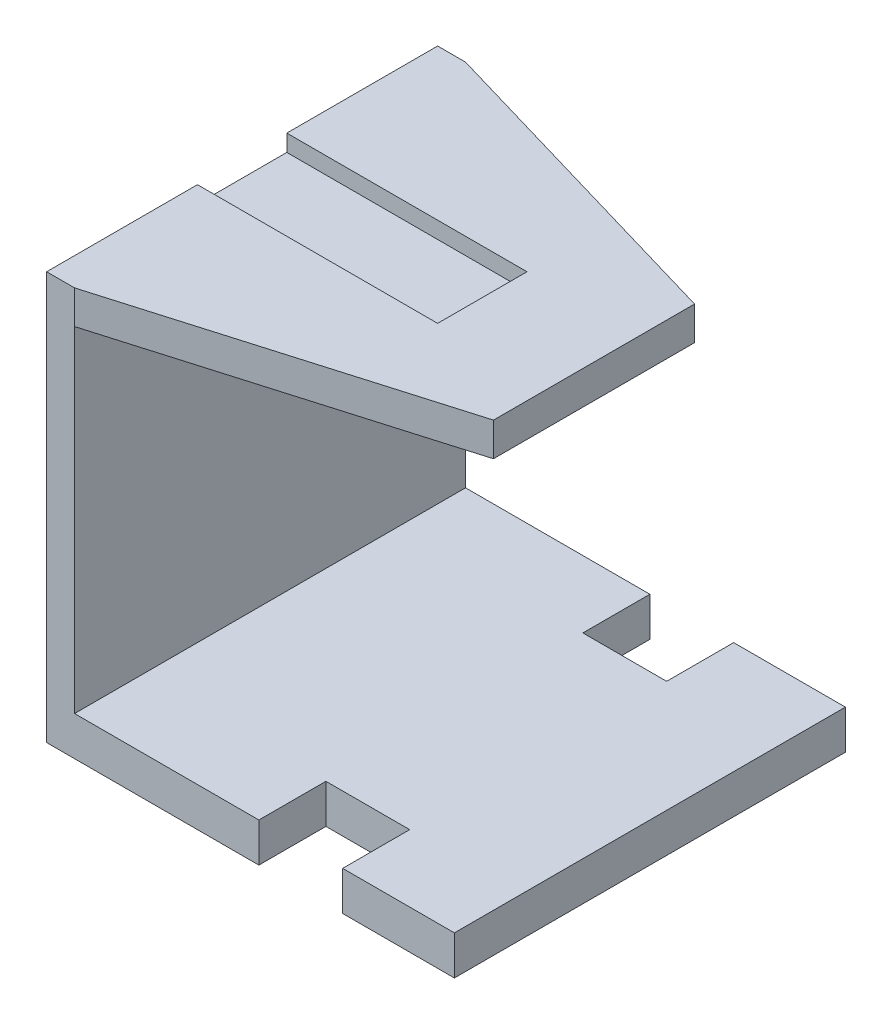
SolidWorks part; units mm, degrees
ref_plane "Спереди" through (0, 0, 0) normal (0, 0, 1) x (1, 0, 0)
ref_plane "Сверху" through (0, 0, 0) normal (0, 1, 0) x (1, 0, 0)
ref_plane "Справа" through (0, 0, 0) normal (1, 0, 0) x (0, 0, -1)
sketch "Эскиз1" plane through (0, 0, 0) normal (0, 0, 1) x (1, 0, 0)
  line L1 (0, 0) -> (75, 0)
  line L2 (0, 0) -> (0, 7)
  line L3 (0, 7) -> (75, 7)
  line L4 (75, 0) -> (75, 7)
  line L5 (0, 7) -> (7, 7)
  line L6 (0, 7) -> (0, 67)
  line L7 (0, 67) -> (7, 67)
  line L8 (7, 7) -> (7, 67)
  dimension "D1" = 75
  dimension "D2" = 7
  dimension "D3" = 60
extrude "Бобышка-Вытянуть1" add sketch "Эскиз1" along normal blind 35 contours L3 L8 L7 L6 | L1 L4 L3 L2
sketch "Эскиз2" plane through (0, 67, 0) normal (0, 1, 0) x (1, 0, 0)
  line L0 (0, -35) -> (65, -35)
  line L1 (7, -35) -> (75, -35) construction
  line L2 (65, -35) -> (65, -17)
  line L3 (65, -17) -> (7, 0)
  line L4 (7, 0) -> (0, 0)
  line L5 (0, 0) -> (0, -35)
  dimension "D1" = 65
  dimension "D2" = 17
extrude "Бобышка-Вытянуть2" add sketch "Эскиз2" along normal blind 6
sketch "Эскиз3" plane through (0, 73, 0) normal (0, 1, 0) x (1, 0, 0)
  line L1 (0, -35) -> (45, -35)
  line L2 (0, -35) -> (0, -27)
  line L3 (0, -27) -> (45, -27)
  line L4 (45, -35) -> (45, -27)
  dimension "D1" = 45
  dimension "D2" = 8
extrude "Вырез-Вытянуть1" cut sketch "Эскиз3" against normal blind 3
sketch "Эскиз4" plane through (0, 7, 0) normal (0, 1, 0) x (1, 0, 0)
  line L0 (7, 0) -> (75, 0) construction
  line L1 (55, 0) -> (40, 0)
  line L2 (55, 0) -> (55, -12)
  line L3 (55, -12) -> (40, -12)
  line L4 (40, 0) -> (40, -12)
  line L5 (75, -35) -> (75, 0) construction
  dimension "D1" = 20
  dimension "D2" = 15
  dimension "D3" = 12
extrude "Вырез-Вытянуть2" cut sketch "Эскиз4" against normal through all
mirror "Зеркальное отражение1" about plane through (0, 0, 35) normal (0, 0, 1) of "Вырез-Вытянуть2", "Вырез-Вытянуть1", "Бобышка-Вытянуть2", "Бобышка-Вытянуть1"
sketch "Эскиз5" plane through (0, 0, 0) normal (-1, 0, 0) x (0, 0, 1)
  line L8 (70, 73) -> (43, 73)
  line L9 (43, 73) -> (43, 70)
  line L10 (43, 70) -> (27, 70)
  line L11 (27, 70) -> (27, 73)
  line L12 (27, 73) -> (0, 73)
  line L13 (0, 73) -> (0, 0)
  line L14 (0, 0) -> (70, 0)
  line L15 (70, 0) -> (70, 73)
  line L16 (70, 73) -> (43, 73)
  line L17 (43, 73) -> (43, 70)
  line L18 (43, 70) -> (27, 70)
  line L19 (27, 70) -> (27, 73)
  line L20 (27, 73) -> (0, 73)
  line L21 (0, 73) -> (0, 0)
  line L22 (0, 0) -> (70, 0)
  line L23 (70, 0) -> (70, 73)
  dimension "D1" = 0
extrude "Вырез-Вытянуть3" cut sketch "Эскиз5" against normal blind 2
